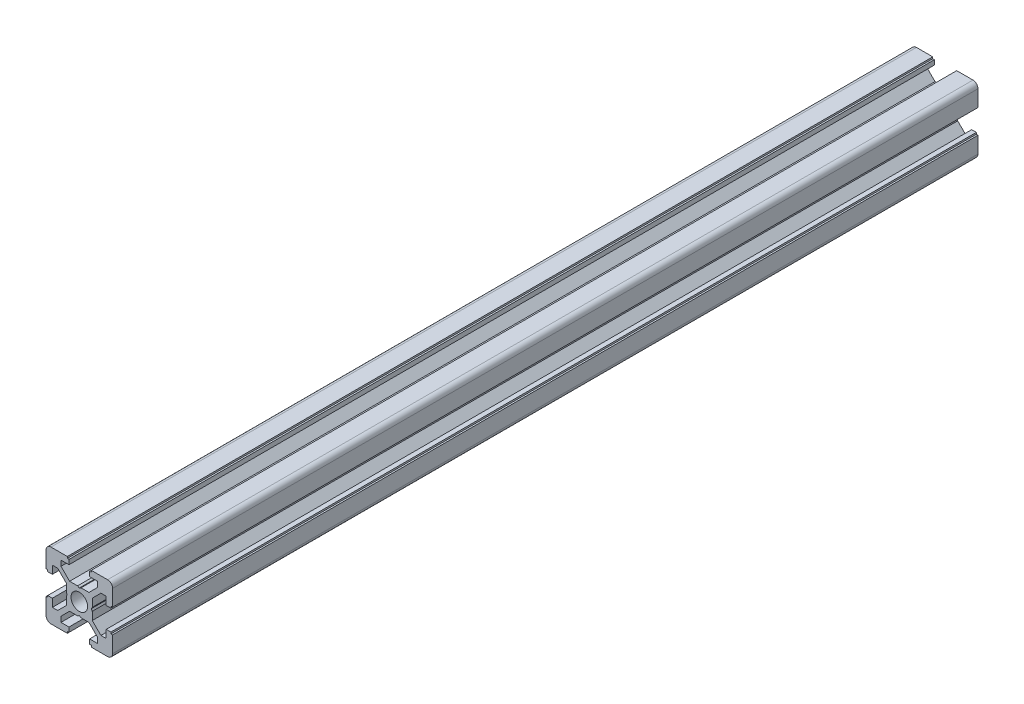
SolidWorks part; units mm, degrees
ref_plane "前视基准面" through (0, 0, 0) normal (0, 0, 1) x (1, 0, 0)
ref_plane "上视基准面" through (0, 0, 0) normal (0, 1, 0) x (1, 0, 0)
ref_plane "右视基准面" through (0, 0, 0) normal (1, 0, 0) x (0, 0, -1)
sketch "草图28" plane through (0, 0, 0) normal (0, 0, 1) x (1, 0, 0)
  line B0 (0, 11.0182) -> (0, -11.0182) construction
  line B1 (-11.0182, 0) -> (11.0182, 0) construction
  line B2 (-3.9, -0.5196) -> (-3.9, -2.9101)
  line B3 (-3.9, -2.9101) -> (-6.4899, -5.5)
  line B4 (-6.4899, -5.5) -> (-8.1, -5.5)
  line B5 (-8.1, -5.5) -> (-8.1, -3.1)
  line B6 (-8.1, -3.1) -> (-9.5, -3.1)
  line B7 (-9.5, -3.1) -> (-9.5, -3.6)
  line B8 (-9.5, -3.6) -> (-10, -3.6)
  line B9 (-10, -3.6) -> (-10, -8.5)
  line B10 (-8.5, -10) -> (-3.6, -10)
  line B11 (-3.6, -10) -> (-3.6, -9.5)
  line B12 (-3.6, -9.5) -> (-3.1, -9.5)
  line B13 (-3.1, -9.5) -> (-3.1, -8.1)
  line B14 (-3.1, -8.1) -> (-5.5, -8.1)
  line B15 (-5.5, -8.1) -> (-5.5, -6.4899)
  line B16 (-5.5, -6.4899) -> (-2.9101, -3.9)
  line B17 (-2.9101, -3.9) -> (-0.5196, -3.9)
  line B18 (-0.5196, -3.9) -> (0, -3.6)
  line B19 (0, -3.6) -> (0.5196, -3.9)
  line B20 (0.5196, -3.9) -> (2.9101, -3.9)
  line B21 (2.9101, -3.9) -> (5.5, -6.4899)
  line B22 (5.5, -6.4899) -> (5.5, -8.1)
  line B23 (5.5, -8.1) -> (3.1, -8.1)
  line B24 (3.1, -8.1) -> (3.1, -9.5)
  line B25 (3.1, -9.5) -> (3.6, -9.5)
  line B26 (3.6, -9.5) -> (3.6, -10)
  line B27 (3.6, -10) -> (8.5, -10)
  line B28 (10, -8.5) -> (10, -3.6)
  line B29 (10, -3.6) -> (9.5, -3.6)
  line B30 (9.5, -3.6) -> (9.5, -3.1)
  line B31 (9.5, -3.1) -> (8.1, -3.1)
  line B32 (8.1, -3.1) -> (8.1, -5.5)
  line B33 (8.1, -5.5) -> (6.4899, -5.5)
  line B34 (6.4899, -5.5) -> (3.9, -2.9101)
  line B35 (3.9, -2.9101) -> (3.9, -0.5196)
  line B36 (3.9, -0.5196) -> (3.6, 0)
  line B37 (3.6, 0) -> (3.9, 0.5196)
  line B38 (3.9, 0.5196) -> (3.9, 2.9101)
  line B39 (3.9, 2.9101) -> (6.4899, 5.5)
  line B40 (6.4899, 5.5) -> (8.1, 5.5)
  line B41 (8.1, 5.5) -> (8.1, 3.1)
  line B42 (8.1, 3.1) -> (9.5, 3.1)
  line B43 (9.5, 3.1) -> (9.5, 3.6)
  line B44 (9.5, 3.6) -> (10, 3.6)
  line B45 (10, 3.6) -> (10, 8.5)
  line B46 (8.5, 10) -> (3.6, 10)
  line B47 (3.6, 10) -> (3.6, 9.5)
  line B48 (3.6, 9.5) -> (3.1, 9.5)
  line B49 (3.1, 9.5) -> (3.1, 8.1)
  line B50 (3.1, 8.1) -> (5.5, 8.1)
  line B51 (5.5, 8.1) -> (5.5, 6.4899)
  line B52 (5.5, 6.4899) -> (2.9101, 3.9)
  line B53 (2.9101, 3.9) -> (0.5196, 3.9)
  line B54 (0.5196, 3.9) -> (0, 3.6)
  line B55 (0, 3.6) -> (-0.5196, 3.9)
  line B56 (-0.5196, 3.9) -> (-2.9101, 3.9)
  line B57 (-2.9101, 3.9) -> (-5.5, 6.4899)
  line B58 (-5.5, 6.4899) -> (-5.5, 8.1)
  line B59 (-5.5, 8.1) -> (-3.1, 8.1)
  line B60 (-3.1, 8.1) -> (-3.1, 9.5)
  line B61 (-3.1, 9.5) -> (-3.6, 9.5)
  line B62 (-3.6, 9.5) -> (-3.6, 10)
  line B63 (-3.6, 10) -> (-8.5, 10)
  line B64 (-10, 8.5) -> (-10, 3.6)
  line B65 (-10, 3.6) -> (-9.5, 3.6)
  line B66 (-9.5, 3.6) -> (-9.5, 3.1)
  line B67 (-9.5, 3.1) -> (-8.1, 3.1)
  line B68 (-8.1, 3.1) -> (-8.1, 5.5)
  line B69 (-8.1, 5.5) -> (-6.4899, 5.5)
  line B70 (-6.4899, 5.5) -> (-3.9, 2.9101)
  line B71 (-3.9, 2.9101) -> (-3.9, 0.5196)
  line B72 (-3.9, 0.5196) -> (-3.6, 0)
  line B73 (-3.6, 0) -> (-3.9, -0.5196)
  circle B74 centre (0, 0) radius 2.5
  arc B75 (-10, -8.5) -> (-8.5, -10) centre (-8.5, -8.5) ccw
  arc B76 (8.5, -10) -> (10, -8.5) centre (8.5, -8.5) ccw
  arc B77 (10, 8.5) -> (8.5, 10) centre (8.5, 8.5) ccw
  arc B78 (-8.5, 10) -> (-10, 8.5) centre (-8.5, 8.5) ccw
sketch_block_instance "块1-1"
sketch_block "块1"
extrude "凸台-拉伸1" add sketch "草图28" along normal blind 260
cosmetic thread "装饰螺纹线1" [suppressed] parameters "D1"=15, "D2"=6
cosmetic thread "装饰螺纹线2" [suppressed] parameters "D1"=15, "D2"=6
ref_plane "基准面1" through (0, 0, 260) normal (0, 0, 1) x (1, 0, 0)
ref_plane "基准面2" through (0, 10, 0) normal (0, 1, 0) x (1, 0, 0)
ref_plane "基准面3" through (0, -10, 0) normal (0, 1, 0) x (1, 0, 0)
ref_plane "基准面4" through (10, 0, 0) normal (1, 0, 0) x (0, 0, -1)
ref_plane "基准面5" through (-10, 0, 0) normal (1, 0, 0) x (0, 0, -1)
sketch "草图19" plane through (0, 0, 0) normal (0, 0, 1) x (1, 0, 0)
  line L0 (0, 0) -> (0, 11.6901) construction
  line L1 (0, 0) -> (10.3437, 0) construction
sketch "草图20" plane through (0, 0, 0) normal (0, 1, 0) x (1, 0, 0)
  line L0 (0, 0) -> (0, 3.5576) construction
ref_point "点1"
sketch "草图2" [suppressed] plane through (0, 0, 0) normal (1, 0, 0) x (0, 0, -1)
  line L0 (-280, -10) -> (-260, 10)
  line L1 (11, -10) -> (-11, -10) construction
  line L2 (11, 10) -> (-11, 10) construction
  line L3 (-260, 10) -> (-280, 10)
  line L4 (-280, 11) -> (-280, -11) construction
  line L5 (-280, 10) -> (-280, -10)
  dimension "D1" = 45
extrude "切除-拉伸1" [suppressed] cut sketch "草图2" against normal through all and the other way through all
sketch "草图3" [suppressed] plane through (0, 0, 0) normal (1, 0, 0) x (0, 0, -1)
  line L0 (0, -10) -> (-20, 10)
  line L1 (11, -10) -> (-11, -10) construction
  line L2 (11, 10) -> (-11, 10) construction
  line L3 (-20, 10) -> (0, 10)
  line L4 (0, 10) -> (0, -10)
  line L5 (0, 11) -> (0, -11) construction
  dimension "D1" = 45
extrude "切除-拉伸2" [suppressed] cut sketch "草图3" against normal through all and the other way through all
sketch "草图4" [suppressed] plane through (0, 0, 0) normal (1, 0, 0) x (0, 0, -1)
  line L0 (-280, 10) -> (-260, -10)
  line L1 (11, 10) -> (-11, 10) construction
  line L2 (-280, 11) -> (-280, -11) construction
  line L3 (11, -10) -> (-11, -10) construction
  line L4 (-260, -10) -> (-280, -10)
  line L5 (-280, -10) -> (-280, 10)
  dimension "D1" = 45
extrude "切除-拉伸3" [suppressed] cut sketch "草图4" against normal through all and the other way through all
sketch "草图5" [suppressed] plane through (0, 0, 0) normal (1, 0, 0) x (0, 0, -1)
  line L0 (0, 10) -> (-20, -10)
  line L1 (11, 10) -> (-11, 10) construction
  line L2 (11, -10) -> (-11, -10) construction
  line L3 (-20, -10) -> (0, -10)
  line L4 (0, -10) -> (0, 10)
  line L5 (0, 11) -> (0, -11) construction
  dimension "D1" = 45
extrude "切除-拉伸4" [suppressed] cut sketch "草图5" against normal through all and the other way through all
sketch "草图6" [suppressed] plane through (0, 0, 0) normal (0, 1, 0) x (1, 0, 0)
  line L0 (-10, -280) -> (10, -260)
  line L1 (-10, -11) -> (-10, 11) construction
  line L2 (-11, -280) -> (11, -280) construction
  line L3 (10, -11) -> (10, 11) construction
  line L4 (10, -260) -> (10, -280)
  line L5 (10, -280) -> (-10, -280)
  dimension "D1" = 45
extrude "切除-拉伸5" [suppressed] cut sketch "草图6" against normal through all and the other way through all
sketch "草图7" [suppressed] plane through (0, 0, 0) normal (0, 1, 0) x (1, 0, 0)
  line L0 (-10, 0) -> (10, -20)
  line L1 (-10, -11) -> (-10, 11) construction
  line L2 (10, -11) -> (10, 11) construction
  line L3 (10, -20) -> (10, 0)
  line L4 (-11, 0) -> (11, 0) construction
  line L5 (10, 0) -> (-10, 0)
  dimension "D1" = 45
extrude "切除-拉伸6" [suppressed] cut sketch "草图7" against normal through all and the other way through all
sketch "草图8" [suppressed] plane through (0, 0, 0) normal (0, 1, 0) x (1, 0, 0)
  line L0 (-10, -260) -> (10, -280)
  line L1 (-10, -11) -> (-10, 11) construction
  line L2 (10, -11) -> (10, 11) construction
  line L3 (-11, -280) -> (11, -280) construction
  line L4 (10, -280) -> (-10, -280)
  line L5 (-10, -280) -> (-10, -260)
  dimension "D1" = 45
extrude "切除-拉伸7" [suppressed] cut sketch "草图8" against normal through all and the other way through all
sketch "草图9" [suppressed] plane through (0, 0, 0) normal (0, 1, 0) x (1, 0, 0)
  line L0 (10, 0) -> (-10, -20)
  line L1 (10, -11) -> (10, 11) construction
  line L2 (-11, 0) -> (11, 0) construction
  line L3 (-10, -11) -> (-10, 11) construction
  line L4 (-10, -20) -> (-10, 0)
  line L5 (-10, 0) -> (10, 0)
  dimension "D1" = 45
extrude "切除-拉伸8" [suppressed] cut sketch "草图9" against normal through all and the other way through all
sketch "草图10" [suppressed] plane through (10, -3.64, 139.7) normal (1, 0, 0) x (0, 0, -1)
  line L1 (-140.3, 14.64) -> (-140.3, -7.36) construction
  circle A0 centre (-127.3, 3.64) radius 6.25
  dimension "D1" = 12.5
  dimension "D2" = 13
extrude "切除-拉伸9" [suppressed] cut sketch "草图10" against normal blind 9
sketch "草图11" [suppressed] plane through (10, 0, 0) normal (1, 0, 0) x (0, 0, -1)
  circle A0 centre (-13, 0) radius 6.25
  dimension "D1" = 12.5
  dimension "D2" = 13
extrude "切除-拉伸10" [suppressed] cut sketch "草图11" against normal blind 9
sketch "草图12" [suppressed] plane through (0, 0, 0) normal (0, 1, 0) x (1, 0, 0)
  line L0 (-10, -11) -> (-10, 11) construction
  line L1 (-10, -267) -> (-1, -267)
  line L2 (-10, -267) -> (-10, -260.75)
  line L3 (-10, -260.75) -> (-1, -260.75)
  line L4 (-1, -267) -> (-1, -260.75)
  line L5 (10, -11) -> (10, 11) construction
  line L6 (10, -267) -> (1, -267)
  line L7 (10, -267) -> (10, -260.75)
  line L8 (10, -260.75) -> (1, -260.75)
  line L9 (1, -267) -> (1, -260.75)
  line L10 (-11, -280) -> (11, -280) construction
  dimension "D1" = 13
  dimension "D2" = 6.25
  dimension "D3" = 9
revolve "切除-旋转1" [suppressed] cut sketch "草图12" angle 360 about L1
sketch "草图13" [suppressed] plane through (0, 0, 0) normal (0, 1, 0) x (1, 0, 0)
  line L0 (-10, -11) -> (-10, 11) construction
  line L1 (-10, -19.25) -> (-1, -19.25)
  line L2 (-10, -19.25) -> (-10, -13)
  line L3 (-10, -13) -> (-1, -13)
  line L4 (-1, -19.25) -> (-1, -13)
  line L5 (10, -11) -> (10, 11) construction
  line L6 (10, -19.25) -> (1, -19.25)
  line L7 (10, -19.25) -> (10, -13)
  line L8 (10, -13) -> (1, -13)
  line L9 (1, -19.25) -> (1, -13)
  dimension "D1" = 13
  dimension "D2" = 6.25
  dimension "D3" = 9
revolve "切除-旋转2" [suppressed] cut sketch "草图13" angle 360 about L3
sketch "草图14" [suppressed] plane through (0, 10, 0) normal (0, 1, 0) x (1, 0, 0)
  line L0 (-11, -280) -> (11, -280) construction
  circle A0 centre (0, -267) radius 6.25
  dimension "D1" = 12.5
  dimension "D2" = 13
extrude "切除-拉伸11" [suppressed] cut sketch "草图14" against normal blind 9
sketch "草图15" [suppressed] plane through (0, 10, 0) normal (0, 1, 0) x (1, 0, 0)
  line L0 (-11, 0) -> (11, 0) construction
  circle A0 centre (0, -13) radius 6.25
  dimension "D1" = 12.5
  dimension "D2" = 13
extrude "切除-拉伸12" [suppressed] cut sketch "草图15" against normal blind 9
sketch "草图16" [suppressed] plane through (0, 0, 0) normal (1, 0, 0) x (0, 0, -1)
  line L0 (11, 10) -> (-11, 10) construction
  line L1 (-267, 10) -> (-260.75, 10)
  line L2 (-267, 10) -> (-267, 1)
  line L3 (-267, 1) -> (-260.75, 1)
  line L4 (-260.75, 10) -> (-260.75, 1)
  line L5 (11, -10) -> (-11, -10) construction
  line L6 (-267, -10) -> (-260.75, -10)
  line L7 (-267, -10) -> (-267, -1)
  line L8 (-267, -1) -> (-260.75, -1)
  line L9 (-260.75, -10) -> (-260.75, -1)
  line L10 (-280, 11) -> (-280, -11) construction
  dimension "D1" = 9
  dimension "D2" = 6.25
  dimension "D3" = 13
revolve "切除-旋转3" [suppressed] cut sketch "草图16" angle 360 about L2
sketch "草图17" [suppressed] plane through (0, 0, 0) normal (1, 0, 0) x (0, 0, -1)
  line L0 (11, 10) -> (-11, 10) construction
  line L1 (-13, 10) -> (-19.25, 10)
  line L2 (-13, 10) -> (-13, 1)
  line L3 (-13, 1) -> (-19.25, 1)
  line L4 (-19.25, 10) -> (-19.25, 1)
  line L5 (11, -10) -> (-11, -10) construction
  line L6 (-13, -10) -> (-19.25, -10)
  line L7 (-13, -10) -> (-13, -1)
  line L8 (-13, -1) -> (-19.25, -1)
  line L9 (-19.25, -10) -> (-19.25, -1)
  dimension "D1" = 6.25
  dimension "D2" = 9
  dimension "D3" = 13
revolve "切除-旋转4" [suppressed] cut sketch "草图17" angle 360 about L2
sketch "草图18" [suppressed] plane through (0, 0, 0) normal (0, 1, 0) x (1, 0, 0)
  line L0 (-10, -230) -> (10, -230)
  line L1 (-10, -11) -> (-10, 11) construction
  line L2 (10, -11) -> (10, 11) construction
  line L3 (10, -230) -> (10, -224.5)
  line L4 (10, -224.5) -> (3.5, -224.5)
  line L5 (3.5, -224.5) -> (3.5, -226.75)
  line L6 (3.5, -226.75) -> (-10, -226.75)
  line L7 (-10, -226.75) -> (-10, -230)
  line L8 (-11, -280) -> (11, -280) construction
  dimension "D1" = 50
  dimension "D2" = 5.5
  dimension "D3" = 3.25
  dimension "D4" = 6.5
revolve "切除-旋转5" [suppressed] cut sketch "草图18" angle 360 about L0
other "表格阵列1" [suppressed] parameters "D0"=70, "D1"=0, "D2"=90, "D3"=0, "D4"=110, "D5"=0, "D6"=130, "D7"=0
sketch "草图21" [suppressed] plane through (0, 0, 0) normal (0, 1, 0) x (1, 0, 0)
  line L0 (-10, -50) -> (10, -50)
  line L1 (-10, -11) -> (-10, 11) construction
  line L2 (10, -11) -> (10, 11) construction
  line L3 (10, -50) -> (10, -55.5)
  line L4 (10, -55.5) -> (3.5, -55.5)
  line L5 (3.5, -55.5) -> (3.5, -53.25)
  line L6 (3.5, -53.25) -> (-10, -53.25)
  line L7 (-10, -53.25) -> (-10, -50)
  dimension "D1" = 5.5
  dimension "D2" = 3.25
  dimension "D3" = 6.5
  dimension "D4" = 50
revolve "切除-旋转6" [suppressed] cut sketch "草图21" angle 360 about L0
other "表格阵列2" [suppressed] parameters "D0"=70, "D1"=0, "D2"=90, "D3"=0, "D4"=110, "D5"=0, "D6"=130, "D7"=0
sketch "草图22" [suppressed] plane through (0, 0, 0) normal (1, 0, 0) x (0, 0, -1)
  line L0 (-230, 10) -> (-230, -10)
  line L1 (11, 10) -> (-11, 10) construction
  line L2 (11, -10) -> (-11, -10) construction
  line L3 (-230, -10) -> (-226.75, -10)
  line L4 (-226.75, -10) -> (-226.75, 3.5)
  line L5 (-226.75, 3.5) -> (-224.5, 3.5)
  line L6 (-224.5, 3.5) -> (-224.5, 10)
  line L7 (-224.5, 10) -> (-230, 10)
  line L8 (-280, 11) -> (-280, -11) construction
  dimension "D1" = 5.5
  dimension "D2" = 3.25
  dimension "D3" = 6.5
  dimension "D4" = 50
revolve "切除-旋转7" [suppressed] cut sketch "草图22" angle 360 about L0
other "表格阵列3" [suppressed] parameters "D0"=70, "D1"=0, "D2"=90, "D3"=0, "D4"=110, "D5"=0, "D6"=130, "D7"=0
sketch "草图23" [suppressed] plane through (0, 0, 0) normal (1, 0, 0) x (0, 0, -1)
  line L0 (-50, 10) -> (-55.5, 10)
  line L1 (11, 10) -> (-11, 10) construction
  line L2 (-55.5, 10) -> (-55.5, 3.5)
  line L3 (-55.5, 3.5) -> (-53.25, 3.5)
  line L4 (-53.25, 3.5) -> (-53.25, -10)
  line L5 (11, -10) -> (-11, -10) construction
  line L6 (-53.25, -10) -> (-50, -10)
  line L7 (-50, -10) -> (-50, 10)
  dimension "D1" = 5.5
  dimension "D2" = 3.25
  dimension "D3" = 6.5
  dimension "D4" = 50
revolve "切除-旋转8" [suppressed] cut sketch "草图23" angle 360 about L7
other "表格阵列4" [suppressed] parameters "D0"=70, "D1"=0, "D2"=90, "D3"=0, "D4"=110, "D5"=0, "D6"=130, "D7"=0
sketch "草图24" [suppressed] plane through (10, 0, 0) normal (1, 0, 0) x (0, 0, -1)
  line L0 (-280, 11) -> (-280, -11) construction
  circle A0 centre (-240, 0) radius 3.25
  dimension "D1" = 6.5
  dimension "D2" = 40
extrude "切除-拉伸13" [suppressed] cut sketch "草图24" against normal through all
other "表格阵列5" [suppressed] parameters "D0"=60, "D1"=0, "D2"=80, "D3"=0, "D4"=100, "D5"=0, "D6"=120, "D7"=0
sketch "草图25" [suppressed] plane through (10, 0, 0) normal (1, 0, 0) x (0, 0, -1)
  circle A0 centre (-40, 0) radius 3.25
  dimension "D1" = 6.5
  dimension "D2" = 40
extrude "切除-拉伸14" [suppressed] cut sketch "草图25" against normal through all
other "表格阵列6" [suppressed] parameters "D0"=60, "D1"=0, "D2"=80, "D3"=0, "D4"=100, "D5"=0, "D6"=120, "D7"=0
sketch "草图26" [suppressed] plane through (0, 10, 0) normal (0, 1, 0) x (1, 0, 0)
  line L0 (-11, -280) -> (11, -280) construction
  circle A0 centre (0, -240) radius 3.25
  dimension "D1" = 6.5
  dimension "D2" = 40
extrude "切除-拉伸15" [suppressed] cut sketch "草图26" against normal through all
other "表格阵列7" [suppressed] parameters "D0"=60, "D1"=0, "D2"=80, "D3"=0, "D4"=100, "D5"=0, "D6"=120, "D7"=0
sketch "草图27" [suppressed] plane through (0, 10, 0) normal (0, 1, 0) x (1, 0, 0)
  circle A0 centre (0, -40) radius 3.25
  dimension "D1" = 6.5
  dimension "D2" = 40
extrude "切除-拉伸16" [suppressed] cut sketch "草图27" against normal through all
other "表格阵列8" [suppressed] parameters "D0"=60, "D1"=0, "D2"=80, "D3"=0, "D4"=100, "D5"=0, "D6"=120, "D7"=0
sketch "草图29" [suppressed] plane through (0, 0, 0) normal (0, 1, 0) x (1, 0, 0)
  line L0 (-10, -230) -> (-10, -224.5)
  line L1 (-10, -224.5) -> (-3.5, -224.5)
  line L2 (-3.5, -224.5) -> (-3.5, -226.75)
  line L3 (-3.5, -226.75) -> (10, -226.75)
  line L4 (10, -226.75) -> (10, -230)
  line L5 (10, -230) -> (-10, -230)
  line L6 (-10, -11) -> (-10, 11) construction
  line L7 (10, -11) -> (10, 11) construction
  line L8 (-11, -280) -> (11, -280) construction
  dimension "D1" = 3.25
  dimension "D2" = 5.5
  dimension "D3" = 6.5
  dimension "D4" = 50
revolve "切除-旋转9" [suppressed] cut sketch "草图29" angle 360 about L5
other "表格阵列9" [suppressed] parameters "D0"=70, "D1"=0, "D2"=90, "D3"=0, "D4"=110, "D5"=0, "D6"=130, "D7"=0
sketch "草图30" [suppressed] plane through (0, 0, 0) normal (0, 1, 0) x (1, 0, 0)
  line L0 (10, -50) -> (10, -53.25)
  line L1 (10, -53.25) -> (-3.5, -53.25)
  line L2 (-3.5, -53.25) -> (-3.5, -55.5)
  line L3 (-3.5, -55.5) -> (-10, -55.5)
  line L4 (-10, -55.5) -> (-10, -50)
  line L5 (-10, -50) -> (10, -50)
  line L6 (-10, -11) -> (-10, 11) construction
  line L7 (10, -11) -> (10, 11) construction
  dimension "D1" = 5.5
  dimension "D2" = 6.5
  dimension "D3" = 3.25
  dimension "D4" = 50
revolve "切除-旋转10" [suppressed] cut sketch "草图30" angle 360 about L5
other "表格阵列10" [suppressed] parameters "D0"=70, "D1"=0, "D2"=90, "D3"=0, "D4"=110, "D5"=0, "D6"=130, "D7"=0
sketch "草图31" [suppressed] plane through (0, 0, 0) normal (1, 0, 0) x (0, 0, -1)
  line L0 (-230, 10) -> (-226.75, 10)
  line L1 (-226.75, 10) -> (-226.75, -3.5)
  line L2 (-226.75, -3.5) -> (-224.5, -3.5)
  line L3 (-224.5, -3.5) -> (-224.5, -10)
  line L4 (-224.5, -10) -> (-230, -10)
  line L5 (-230, -10) -> (-230, 10)
  line L6 (11, 10) -> (-11, 10) construction
  line L7 (11, -10) -> (-11, -10) construction
  line L8 (-280, 11) -> (-280, -11) construction
  dimension "D1" = 3.25
  dimension "D2" = 5.5
  dimension "D3" = 6.5
  dimension "D4" = 50
revolve "切除-旋转11" [suppressed] cut sketch "草图31" angle 360 about L5
other "表格阵列11" [suppressed] parameters "D0"=70, "D1"=0, "D2"=90, "D3"=0, "D4"=110, "D5"=0, "D6"=130, "D7"=0
sketch "草图32" [suppressed] plane through (0, 0, 0) normal (1, 0, 0) x (0, 0, -1)
  line L0 (-50, 10) -> (-53.25, 10)
  line L1 (-53.25, 10) -> (-53.25, -3.5)
  line L2 (-53.25, -3.5) -> (-55.5, -3.5)
  line L3 (-55.5, -3.5) -> (-55.5, -10)
  line L4 (-55.5, -10) -> (-50, -10)
  line L5 (-50, -10) -> (-50, 10)
  line L6 (11, 10) -> (-11, 10) construction
  line L7 (11, -10) -> (-11, -10) construction
  dimension "D1" = 3.25
  dimension "D2" = 5.5
  dimension "D3" = 6.5
  dimension "D4" = 50
revolve "切除-旋转12" [suppressed] cut sketch "草图32" angle 360 about L5
other "表格阵列12" [suppressed] parameters "D0"=70, "D1"=0, "D2"=90, "D3"=0, "D4"=110, "D5"=0, "D6"=130, "D7"=0
